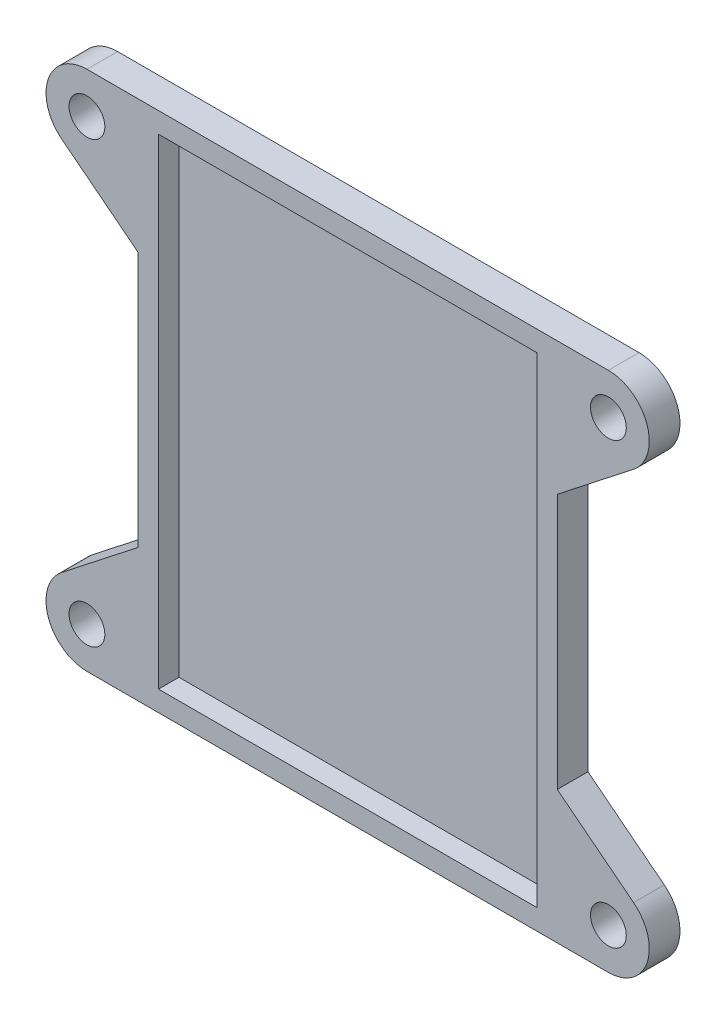
SolidWorks part; units mm, degrees
ref_plane "Front Plane" through (0, 0, 0) normal (0, 0, 1) x (1, 0, 0)
ref_plane "Top Plane" through (0, 0, 0) normal (0, 1, 0) x (1, 0, 0)
ref_plane "Right Plane" through (0, 0, 0) normal (1, 0, 0) x (0, 0, -1)
sketch "Sketch1" plane through (0, 0, 0) normal (0, 0, 1) x (1, 0, 0)
  line L1 (-20.5, -25.5) -> (20.5, -25.5)
  line L2 (-20.5, -25.5) -> (-20.5, 25.5)
  line L3 (-20.5, 25.5) -> (20.5, 25.5)
  line L4 (20.5, -25.5) -> (20.5, 25.5)
  line L5 (-20.5, -25.5) -> (20.5, 25.5) construction
  line L6 (-20.5, 25.5) -> (20.5, -25.5) construction
  point P0 (0, 0)
  dimension "D1" = 41
  dimension "D2" = 51
extrude "Boss-Extrude1" add sketch "Sketch1" along normal blind 3
sketch "Sketch2" plane through (0, 0, 3) normal (0, 0, 1) x (1, 0, 0)
  line L8 (18.5, -23.5) -> (18.5, 23.5)
  line L9 (18.5, 23.5) -> (-18.5, 23.5)
  line L10 (-18.5, 23.5) -> (-18.5, -23.5)
  line L11 (-18.5, -23.5) -> (18.5, -23.5)
  line L12 (18.5, -23.5) -> (18.5, 23.5)
  line L13 (18.5, 23.5) -> (-18.5, 23.5)
  line L14 (-18.5, 23.5) -> (-18.5, -23.5)
  line L15 (-18.5, -23.5) -> (18.5, -23.5)
  dimension "D1" = 2
extrude "Cut-Extrude1" cut sketch "Sketch2" against normal blind 2
sketch "Sketch4" plane through (0, 0, 0) normal (0, 0, 1) x (1, 0, 0)
  line L0 (25.5, 25.5) -> (20.5, 25.5)
  line L1 (20.5, 25.5) -> (20.5, 12.5)
  line L2 (20.5, -25.5) -> (20.5, 25.5) construction
  line L3 (20.5, 12.5) -> (27.9672, 18.3515)
  arc A0 (27.9672, 18.3515) -> (25.5, 25.5) centre (25.5, 21.5) ccw
  circle A1 centre (25.5, 21.5) radius 1.75
  dimension "D1" = 8
  dimension "D4" = 3.5
  dimension "D2" = 13
  dimension "D3" = 5
extrude "Boss-Extrude2" add sketch "Sketch4" along normal blind 3
mirror "Mirror1" about plane through (0, 0, 0) normal (1, 0, 0) of "Boss-Extrude2" second plane through (0, 0, 0) second plane normal (0, 1, 0)
